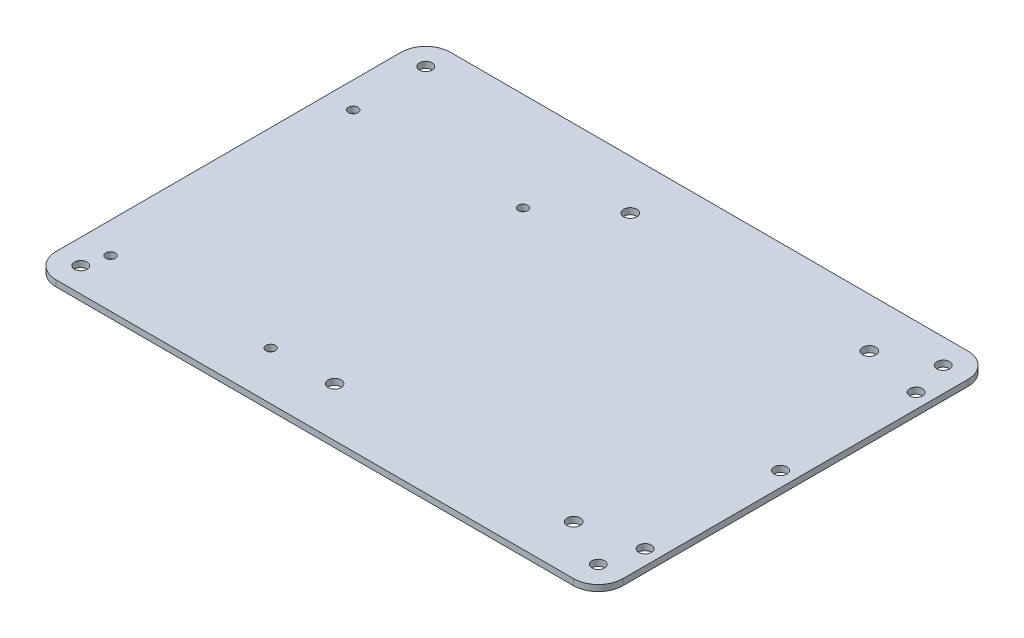
SolidWorks part; units mm, degrees
material "ABS"
ref_plane "Front Plane" through (0, 0, 0) normal (0, 0, 1) x (1, 0, 0)
ref_plane "Top Plane" through (0, 0, 0) normal (0, 1, 0) x (1, 0, 0)
ref_plane "Right Plane" through (0, 0, 0) normal (1, 0, 0) x (0, 0, -1)
sketch "Sketch1" plane through (0, 0, 0) normal (0, 1, 0) x (1, 0, 0)
  line L1 (-73.025, -50.8) -> (73.025, -50.8)
  line L2 (-73.025, -50.8) -> (-73.025, 50.8)
  line L3 (-73.025, 50.8) -> (73.025, 50.8)
  line L4 (73.025, -50.8) -> (73.025, 50.8)
  line L5 (-73.025, -50.8) -> (73.025, 50.8) construction
  line L6 (-73.025, 50.8) -> (73.025, -50.8) construction
  point P0 (0, 0)
  dimension "D1" = 101.6
  dimension "D2" = 146.05
extrude "Boss-Extrude1" add sketch "Sketch1" along normal blind 1.5875
fillet "Fillet1" radius 6.35 4 edges at (-73.025, 0.7937, -50.8) (73.025, 0.7937, -50.8) (-73.025, 0.7937, 50.8) (73.025, 0.7937, 50.8)
hole_wizard "#4 Clearance Hole1" positions "Sketch3" profile "Sketch2" hole size "#4" standard "Ansi Inch"
sketch "Sketch3" plane through (0, 1.5875, 0) normal (0, 1, 0) x (-1, 0, 0)
  point P1 (-66.675, 44.45)
  point P4 (-66.675, -44.45)
  point P7 (66.675, -44.45)
  point P10 (66.675, 44.45)
sketch "Sketch2" plane through (66.675, 1.5875, 44.45) normal (1, 0, 0) x (0, 0, 1)
  line L0 (0, 0) -> (0, 51.7806)
  line L1 (0, 51.7806) -> (1.6319, 50.8)
  line L2 (1.6319, 50.8) -> (1.6319, 0)
  line L5 (1.6319, 0) -> (0, 0)
  line L10 (0, 51.7806) -> (-1.632, 50.8) construction
  line L11 (0, -6.35) -> (0, 107.95) construction
  dimension "Hole Dia." = 3.2639
  dimension "Hole Depth" = 50.8
  dimension "Drill Angle" = 118
sketch "Sketch4" plane through (0, 1.5875, 0) normal (0, 1, 0) x (1, 0, 0)
  line L0 (73.025, -44.45) -> (73.025, 44.45) construction
  line L1 (53.975, -38.1) -> (-7.62, -38.1) construction
  line L2 (53.975, -38.1) -> (53.975, 38.1) construction
  line L3 (53.975, 38.1) -> (-7.62, 38.1) construction
  line L4 (-7.62, -38.1) -> (-7.62, 38.1) construction
  line L5 (53.975, -38.1) -> (-7.62, 38.1) construction
  line L6 (53.975, 38.1) -> (-7.62, -38.1) construction
  point P0 (23.1775, 0)
  dimension "D1" = 61.595
  dimension "D2" = 76.2
  dimension "D3" = 19.05
hole_wizard "M3 Clearance Hole1" positions "Sketch6" profile "Sketch7" hole size "M3" standard "Ansi Metric" end condition up to next
sketch "Sketch6" plane through (0, 1.5875, 0) normal (0, 1, 0) x (-1, 0, 0)
  point P1 (7.62, -38.1)
  point P4 (-53.975, -38.1)
  point P7 (7.62, 38.1)
  point P10 (-53.975, 38.1)
sketch "Sketch7" plane through (-7.62, 1.5875, -38.1) normal (1, 0, 0) x (0, 0, 1)
  line L0 (0, 0) -> (0, 1.5875)
  line L1 (0, 1.5875) -> (1.7, 1.5875)
  line L2 (1.7, 1.5875) -> (1.7, 0)
  line L5 (1.7, 0) -> (0, 0)
  line L11 (0, -6.35) -> (0, 107.95) construction
  dimension "Thru Hole Dia." = 3.4
  dimension "Thru Hole Depth" = 1.5875
hole_wizard "#4 Clearance Hole2" positions "Sketch10" profile "Sketch9" hole size "#4" standard "Ansi Inch" end condition up to next
sketch "Sketch10" plane through (0, 1.5875, 0) normal (0, 1, 0) x (-1, 0, 0)
  line L0 (-69.215, -44.45) -> (-69.215, 44.45) construction
  line L1 (-73.025, 44.45) -> (-73.025, -44.45) construction
  point P0 (-69.215, 0)
  point P9 (-69.215, 34.925)
  point P11 (-69.215, -34.925)
  dimension "D1" = 34.925
  dimension "D2" = 34.925
  dimension "D3" = 3.81
sketch "Sketch9" plane through (69.215, 1.5875, 0) normal (1, 0, 0) x (0, 0, 1)
  line L0 (0, 0) -> (0, 1.5875)
  line L1 (0, 1.5875) -> (1.6319, 1.5875)
  line L2 (1.6319, 1.5875) -> (1.6319, 0)
  line L5 (1.6319, 0) -> (0, 0)
  line L11 (0, -6.35) -> (0, 107.95) construction
  dimension "Thru Hole Dia." = 3.2639
  dimension "Thru Hole Depth" = 1.5875
hole_wizard "#2 Clearance Hole1" positions "Sketch12" profile "Sketch13" hole size "#2" standard "Ansi Inch" end condition up to next
sketch "Sketch12" plane through (0, 0, 0) normal (0, -1, 0) x (1, 0, 0)
  line L0 (-73.025, -44.45) -> (-73.025, 44.45) construction
  line L2 (66.675, -50.8) -> (-66.675, -50.8) construction
  point P0 (-66.3194, -25.4)
  point P1 (-22.5806, -25.4)
  point P3 (-65.0875, 38.3794)
  point P5 (-23.8125, 38.3794)
  dimension "D1" = 6.7056
  dimension "D2" = 43.7388
  dimension "D3" = 7.9375
  dimension "D4" = 63.7794
  dimension "D5" = 41.275
  dimension "D6" = 25.4
sketch "Sketch13" plane through (-66.3194, 0, -25.4) normal (1, 0, 0) x (0, 0, -1)
  line L0 (0, 0) -> (0, 1.5875)
  line L1 (0, 1.5875) -> (1.2192, 1.5875)
  line L2 (1.2192, 1.5875) -> (1.2192, 0)
  line L5 (1.2192, 0) -> (0, 0)
  line L11 (0, -6.35) -> (0, 107.95) construction
  dimension "Thru Hole Dia." = 2.4384
  dimension "Thru Hole Depth" = 1.5875
